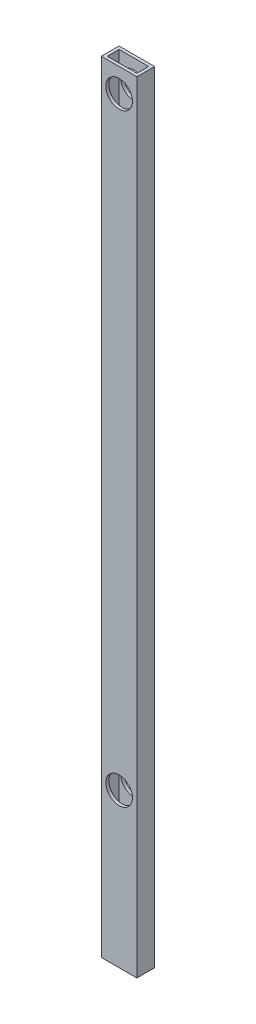
SolidWorks part; units mm, degrees
ref_plane "Front Plane" through (0, 0, 0) normal (0, 0, 1) x (1, 0, 0)
ref_plane "Top Plane" through (0, 0, 0) normal (0, 1, 0) x (1, 0, 0)
ref_plane "Right Plane" through (0, 0, 0) normal (1, 0, 0) x (0, 0, -1)
sketch "Sketch1" plane through (0, 0, 0) normal (0, 1, 0) x (1, 0, 0)
  line L1 (0, 0) -> (38.1, 0)
  line L2 (0, 0) -> (0, 19.05)
  line L3 (0, 19.05) -> (38.1, 19.05)
  line L4 (38.1, 0) -> (38.1, 19.05)
  dimension "D1" = 19.05
  dimension "D2" = 38.1
extrude "Extrude-Thin1" add sketch "Sketch1" along normal blind 838.2 thin contours L1 L4 L3 L2 thin type one direction reverse wall 3.175
sketch "Sketch2" plane through (0, 0, 0) normal (0, 0, 1) x (1, 0, 0)
  line L0 (0, 838.2) -> (0, 0) construction
  line L1 (0, 0) -> (38.1, 0) construction
  circle A0 centre (19.05, 165.1) radius 14.2875
  dimension "D1" = 28.575
  dimension "D2" = 19.05
  dimension "D3" = 165.1
extrude "Cut-Extrude1" cut sketch "Sketch2" against normal through all
sketch "Sketch3" plane through (0, 0, 0) normal (0, 0, 1) x (1, 0, 0)
  line L0 (0, 838.2) -> (0, 0) construction
  line L1 (0, 838.2) -> (38.1, 838.2) construction
  circle A0 centre (19.05, 812.8) radius 14.2875
  dimension "D1" = 19.05
  dimension "D2" = 25.4
extrude "Cut-Extrude2" cut sketch "Sketch3" against normal through all
